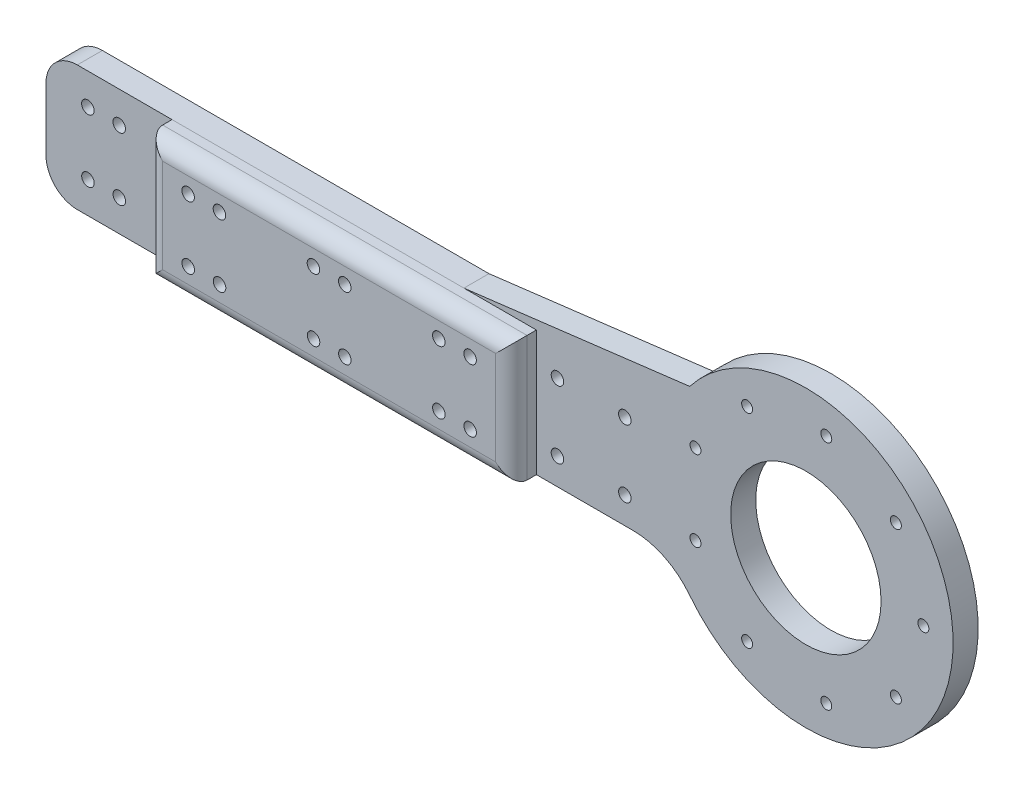
SolidWorks part; units mm, degrees
ref_plane "前视基准面" through (0, 0, 0) normal (0, 0, 1) x (1, 0, 0)
ref_plane "上视基准面" through (0, 0, 0) normal (0, 1, 0) x (1, 0, 0)
ref_plane "右视基准面" through (0, 0, 0) normal (1, 0, 0) x (0, 0, -1)
sketch "草图1" plane through (0, 0, 0) normal (0, 0, 1) x (1, 0, 0)
  line L1 (-100, -20) -> (100, -20)
  line L2 (-100, -20) -> (-100, 20)
  line L3 (-100, 20) -> (100, 20)
  line L4 (100, -20) -> (100, 20) construction
  line L5 (-100, -20) -> (100, 20) construction
  line L6 (-100, 20) -> (100, -20) construction
  line L16 (180.0323, 0) -> (171.259, 24.1045) construction
  line L17 (171.259, 24.1045) -> (149.0441, 36.9303) construction
  line L18 (149.0441, 36.9303) -> (123.7823, 32.476) construction
  line L19 (123.7823, 32.476) -> (107.2939, 12.8258) construction
  line L20 (107.2939, 12.8258) -> (107.2939, -12.8258) construction
  line L21 (107.2939, -12.8258) -> (123.7823, -32.476) construction
  line L22 (123.7823, -32.476) -> (149.0441, -36.9303) construction
  line L23 (149.0441, -36.9303) -> (171.259, -24.1045) construction
  line L24 (171.259, -24.1045) -> (180.0323, 0) construction
  arc A0 (100, 20) -> (100, -20) centre (142.5323, 0) cw
  circle A1 centre (142.5323, 0) radius 24
  circle A2 centre (142.5323, 0) radius 37.5 construction
  circle A12 centre (123.7823, 32.476) radius 1.75
  circle A13 centre (107.2939, 12.8258) radius 1.75
  circle A14 centre (107.2939, -12.8258) radius 1.75
  circle A15 centre (123.7823, -32.476) radius 1.75
  circle A16 centre (149.0441, -36.9303) radius 1.75
  circle A17 centre (171.259, -24.1045) radius 1.75
  circle A18 centre (180.0323, 0) radius 1.75
  circle A19 centre (171.259, 24.1045) radius 1.75
  circle A20 centre (149.0441, 36.9303) radius 1.75
  point P0 (0, 0)
  point P37 (142.5323, 0)
  dimension "D3" = 47
  dimension "D4" = 48
  dimension "D5" = 9
  dimension "D7" = 3.5
  dimension "D1" = 200
  dimension "D2" = 40
  dimension "D6" = 37.5
  dimension "D8" = 25.2618
extrude "凸台-拉伸1" add sketch "草图1" along normal blind 8
fillet "圆角1" radius 10 1 edges at (-100, 20, 4)
fillet "圆角3" radius 10 1 edges at (-100, -20, 4)
sketch "草图3" plane through (0, 0, 8) normal (0, 0, 1) x (1, 0, 0)
  line L5 (0, 0) -> (-100, 0) construction
  line L6 (-100, 10) -> (-100, -10) construction
  circle A0 centre (-86.6375, 10) radius 2
  circle A1 centre (-86.6104, -10) radius 2
  circle A2 centre (-76.6375, 10) radius 2
  circle A3 centre (-76.6104, -10) radius 2
  circle A4 centre (-46.6375, 10) radius 2
  circle A5 centre (-46.6104, -10) radius 2
  circle A6 centre (-36.6375, 10) radius 2
  circle A7 centre (-36.6104, -10) radius 2
  circle A8 centre (-6.6375, 10) radius 2
  circle A9 centre (-6.6104, -10) radius 2
  circle A10 centre (3.3625, 10) radius 2
  circle A11 centre (3.3896, -10) radius 2
  circle A12 centre (33.3625, 10) radius 2
  circle A13 centre (33.3896, -10) radius 2
  circle A14 centre (43.3625, 10) radius 2
  circle A15 centre (43.3896, -10) radius 2
  circle A16 centre (63.2473, 10) radius 2
  circle A17 centre (84.7473, 10) radius 2
  circle A18 centre (84.7473, -11.5) radius 2
  circle A19 centre (63.2473, -11.5) radius 2
  dimension "D1" = 20
  dimension "D6" = 4
  dimension "D7" = 2
  dimension "D9" = 4
  dimension "D2" = 10
  dimension "D3" = 2
  dimension "D4" = 4
  dimension "D5" = 30
  dimension "D8" = 2
fillet "圆角8" radius 23 1 edges at (100, -20, 4)
fillet "圆角9" radius 23 1 edges at (100, 20, 4)
extrude "切除-拉伸1" cut sketch "草图3" against normal through all
sketch "草图6" plane through (0, 0, 8) normal (0, 0, 1) x (1, 0, 0)
  line L0 (33.3888, 20) -> (105.4454, 28.8714)
  line L1 (87.2965, 20) -> (-90, 20) construction
rib "筋1" sketch "草图6" sketch "草图6" thickness 8 extrusion direction parallel to sketch draft on no parameters "D1"=8
sketch "草图11" plane through (0, 0, 8) normal (0, 0, 1) x (1, 0, 0)
  line L0 (-6.6375, 10) -> (3.3896, -10) construction
  line L1 (-90, -20) -> (87.2965, -20) construction
  line L2 (-59.7802, 20) -> (56.5323, 20)
  line L3 (-59.7802, 20) -> (-59.7802, -20)
  line L4 (-59.7802, -20) -> (56.5323, -20)
  line L5 (56.5323, 20) -> (56.5323, -20)
  line L6 (-59.7802, 20) -> (56.5323, -20) construction
  line L7 (-59.7802, -20) -> (56.5323, 20) construction
  circle A0 centre (142.5323, 0) radius 24 construction
  circle A1 centre (-46.6375, 10) radius 2
  circle A2 centre (-36.6375, 10) radius 2
  circle A3 centre (-36.6104, -10) radius 2
  circle A4 centre (-46.6104, -10) radius 2
  circle A5 centre (-6.6375, 10) radius 2
  circle A6 centre (-6.6104, -10) radius 2
  circle A7 centre (3.3896, -10) radius 2
  circle A8 centre (3.3625, 10) radius 2
  circle A9 centre (33.3625, 10) radius 2
  circle A10 centre (43.3625, 10) radius 2
  circle A11 centre (43.3896, -10) radius 2
  circle A12 centre (33.3896, -10) radius 2
  point P4 (-1.6239, 0)
  dimension "D2" = 4
  dimension "D1" = 86
extrude "凸台-拉伸2" add sketch "草图11" along normal blind 8
fillet "圆角11" radius 5 4 edges at (-1.6239, 20, 16) (-1.6239, -20, 16) (56.5323, 0, 16) (-59.7802, 0, 16)
